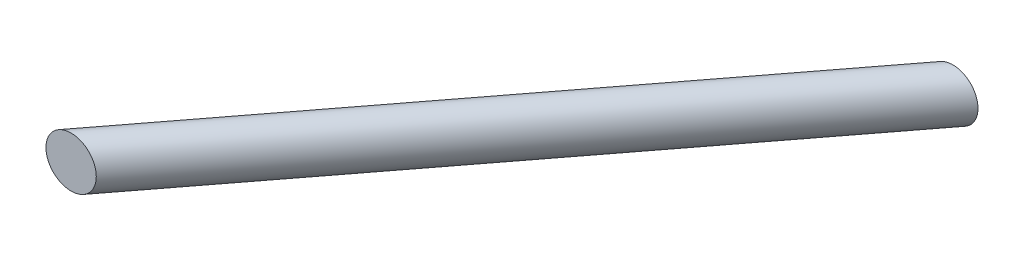
SolidWorks part; units mm, degrees
ref_plane "Front Plane" through (0, 0, 0) normal (0, 0, 1) x (1, 0, 0)
ref_plane "Top Plane" through (0, 0, 0) normal (0, 1, 0) x (1, 0, 0)
ref_plane "Right Plane" through (0, 0, 0) normal (1, 0, 0) x (0, 0, -1)
sketch "Sketch1" plane through (0, 0, 0) normal (0, 1, 0) x (1, 0, 0)
  line L0 (0, 0) -> (0, 51.6353)
  line L1 (0, 0) -> (39.4354, 51.6353)
  line L2 (0, 51.6353) -> (39.4354, 51.6353)
sketch "Sketch5" plane through (0, 0, 0) normal (0, 0, 1) x (1, 0, 0)
  line L0 (0, 2) -> (0, -2) construction
  circle A0 centre (0, 0) radius 2
extrude "Boss-Extrude1" add sketch "Sketch5" along direction (0.607, 0, -0.7947) on the side of the normal blind 50 contours A0
